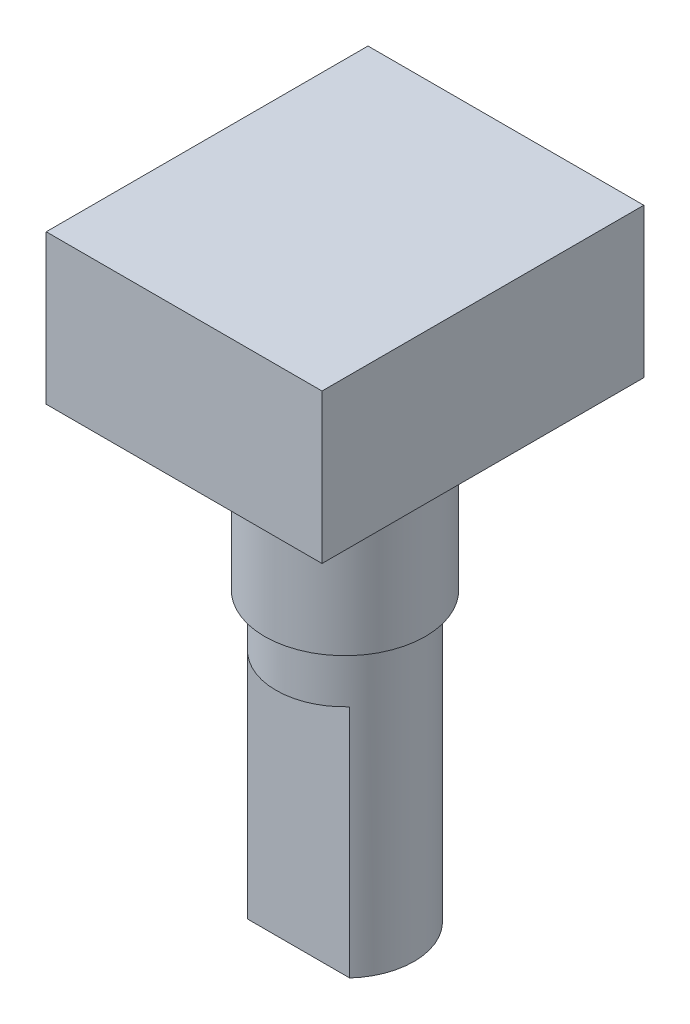
SolidWorks part; units mm, degrees
ref_plane "Front" through (0, 0, 0) normal (0, 0, 1) x (1, 0, 0)
ref_plane "Top" through (0, 0, 0) normal (0, 1, 0) x (1, 0, 0)
ref_plane "Right" through (0, 0, 0) normal (1, 0, 0) x (0, 0, -1)
sketch "Sketch1" plane through (0, 0, 0) normal (0, 1, 0) x (1, 0, 0)
  line L1 (6, -7) -> (-6, -7)
  line L2 (6, -7) -> (6, 7)
  line L3 (6, 7) -> (-6, 7)
  line L4 (-6, -7) -> (-6, 7)
  line L5 (0, 7) -> (0, -7) construction
  line L6 (6, 0) -> (-6, 0) construction
  point P0 (0, 0)
  dimension "D1" = 12
  dimension "D2" = 14
extrude "Boss-Extrude1" add sketch "Sketch1" along normal blind 6.5
sketch "Sketch2" plane through (0, 0, 0) normal (0, -1, 0) x (1, 0, 0)
  circle A0 centre (0, 0) radius 3.5
  dimension "D1" = 7
extrude "Boss-Extrude2" add sketch "Sketch2" along normal blind 7.5
cosmetic thread "Cosmetic Thread1" parameters "D2"=4.891
sketch "Sketch3" plane through (0, -7.5, 0) normal (0, -1, 0) x (1, 0, 0)
  circle A0 centre (0, 0) radius 3
  dimension "D1" = 6
extrude "Boss-Extrude3" add sketch "Sketch3" along normal blind 12.5
sketch "Sketch4" plane through (0, -20, 0) normal (0, -1, 0) x (1, 0, 0)
  line L0 (0, 0) -> (0, 3.5) construction
  line L1 (-2.86, 2.0175) -> (2.86, 2.0175)
  arc A0 (2.86, 2.0175) -> (-2.86, 2.0175) centre (0, 0) ccw
  circle A1 centre (0, 0) radius 3.5 construction
  point P9 (0, 2.0175)
  dimension "D1" = 5.72
extrude "Cut-Extrude1" cut sketch "Sketch4" against normal blind 10.22
